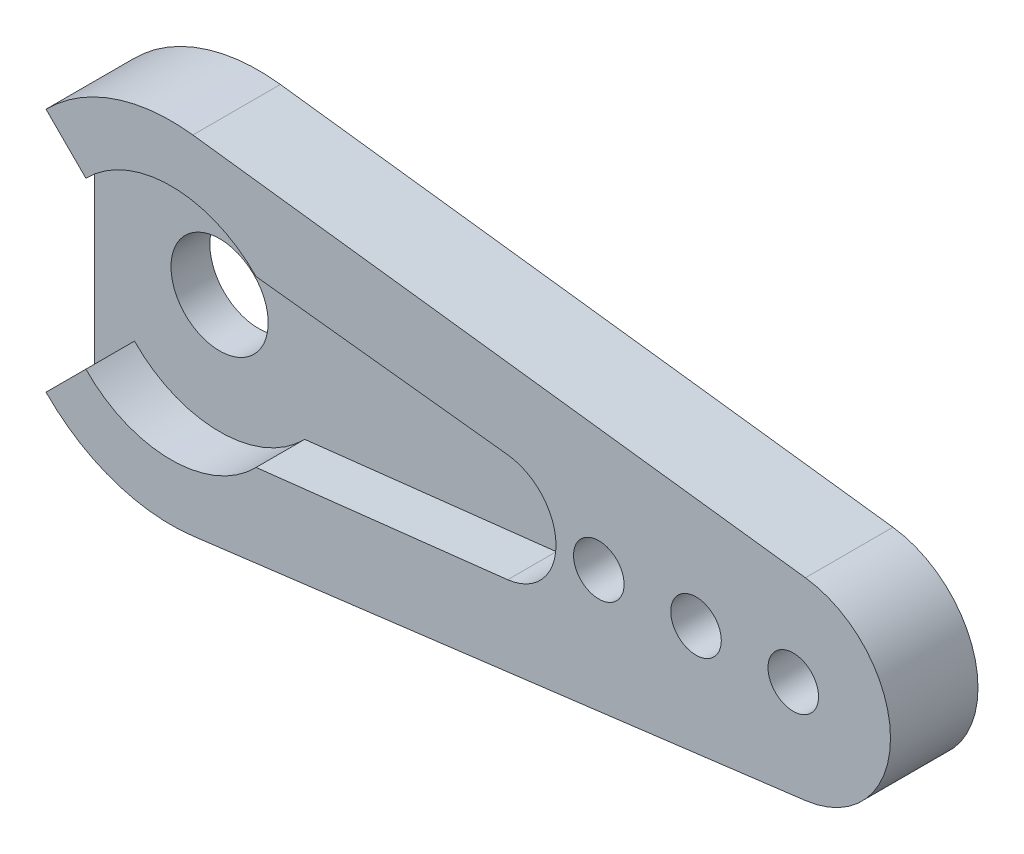
SolidWorks part; units mm, degrees
ref_plane "Front Plane" through (0, 0, 0) normal (0, 0, 1) x (1, 0, 0)
ref_plane "Top Plane" through (0, 0, 0) normal (0, 1, 0) x (1, 0, 0)
ref_plane "Right Plane" through (0, 0, 0) normal (1, 0, 0) x (0, 0, -1)
sketch "Esquisse1" plane through (0, 0, 0) normal (0, 0, 1) x (1, 0, 0)
  line L0 (-4.3758, 4.25) -> (-6.4265, 6.3008)
  line L1 (4.3758, 4.25) -> (17.3156, 2.7822)
  line L2 (17.3156, -2.7822) -> (4.3758, -4.25)
  line L4 (1.125, 8.9294) -> (32.625, 4.9608)
  line L5 (1.125, -8.9294) -> (32.625, -4.9608)
  line L6 (-4.3758, -4.25) -> (-6.4265, -6.3008)
  arc A0 (4.3758, 4.25) -> (-4.3758, 4.25) centre (0, 0) ccw
  arc A1 (17.3156, -2.7822) -> (17.3156, 2.7822) centre (17, 0) ccw
  arc A2 (4.3758, -4.25) -> (-4.3758, -4.25) centre (0, 0) cw
  arc A3 (-6.4265, 6.3008) -> (1.125, 8.9294) centre (0, 0) cw
  arc A4 (32.625, 4.9608) -> (32.625, -4.9608) centre (32, 0) cw
  arc A5 (-6.4265, -6.3008) -> (1.125, -8.9294) centre (0, 0) ccw
  dimension "D2" = 6.1
  dimension "D3" = 2.8
  dimension "D6" = 9
  dimension "D8" = 5
  dimension "D1" = 8.5
  dimension "D4" = 17
  dimension "D7" = 32
extrude "Main" add sketch "Esquisse1" along normal blind 2.5
sketch "Esquisse2" plane through (0, 0, 0) normal (0, 0, -1) x (-1, 0, 0)
  line L0 (-1.125, -8.9294) -> (-32.625, -4.9608)
  line L1 (-1.125, -8.9294) -> (-32.625, -4.9608) construction
  line L3 (-1.125, 8.9294) -> (-32.625, 4.9608)
  line L4 (6.4265, -6.3008) -> (6.4265, 6.3008)
  arc A0 (-32.625, 4.9608) -> (-32.625, -4.9608) centre (-32, 0) ccw construction
  arc A1 (-1.125, -8.9294) -> (6.4265, -6.3008) centre (0, 0) ccw
  circle A2 centre (0, 0) radius 2.5
  arc A3 (6.4265, 6.3008) -> (-1.125, 8.9294) centre (0, 0) ccw
  arc A5 (-32.625, 4.9608) -> (-32.625, -4.9608) centre (-32, 0) ccw
  arc A6 (-1.125, -8.9294) -> (6.4265, -6.3008) centre (0, 0) ccw construction
  dimension "D1" = 5
extrude "OriginalBracket" add sketch "Esquisse2" along normal blind 2
sketch "Esquisse3" plane through (0, 0, 2.5) normal (0, 0, 1) x (1, 0, 0)
  circle A0 centre (32, 0) radius 1.3
  circle A1 centre (22, 0) radius 1.3
  arc A2 (32.625, -4.9608) -> (32.625, 4.9608) centre (32, 0) ccw construction
  circle A3 centre (27, 0) radius 1.3
  point P7 (0, 0)
  dimension "D1" = 2.6
  dimension "D2" = 10
  dimension "D3" = 5
extrude "FixingHole" cut sketch "Esquisse3" against normal through all
